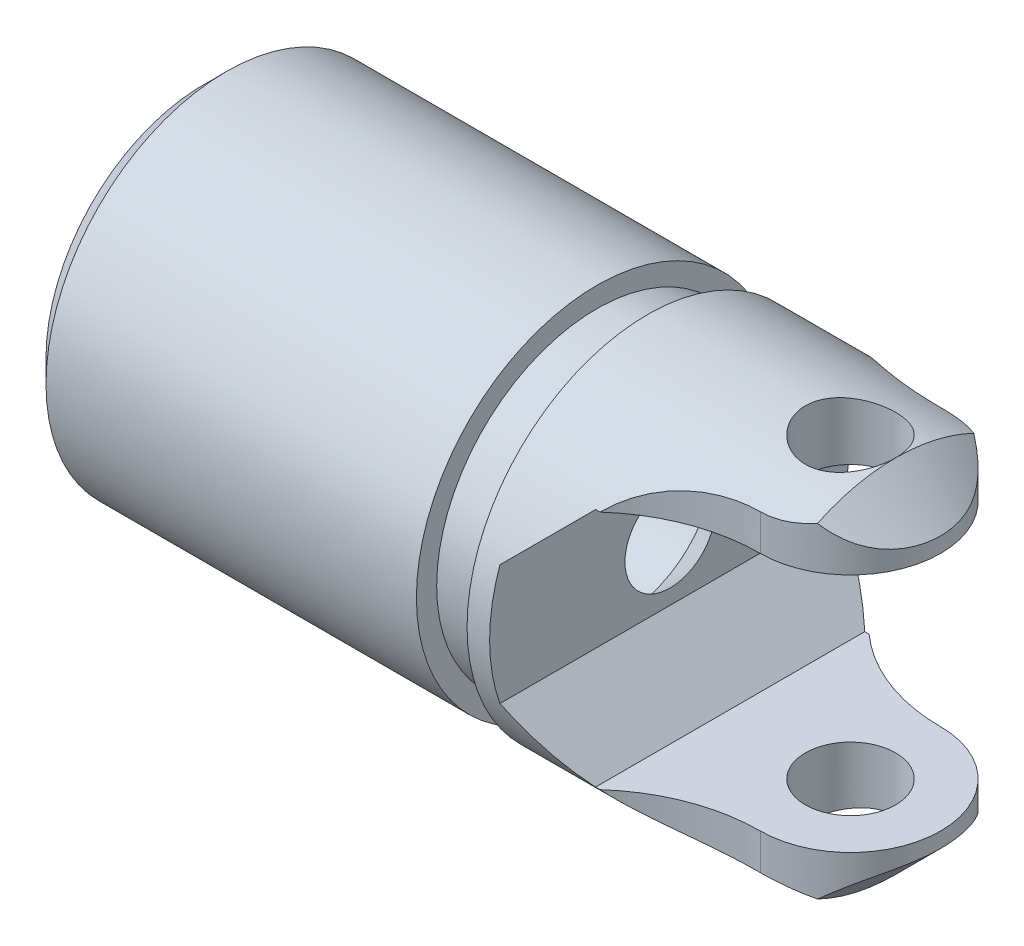
SolidWorks part; units mm, degrees
ref_plane "Front Plane" through (0, 0, 0) normal (0, 0, 1) x (1, 0, 0)
ref_plane "Top Plane" through (0, 0, 0) normal (0, 1, 0) x (1, 0, 0)
ref_plane "Right Plane" through (0, 0, 0) normal (1, 0, 0) x (0, 0, -1)
sketch "Sketch0" plane through (0, 0, 0) normal (0, 1, 0) x (1, 0, 0)
  line L0 (-34.1313, 0) -> (34.1313, 0) construction
  line L1 (-34.1313, 9.525) -> (-34.1313, -9.525) construction
  line L2 (-11.9063, 4.7625) -> (-11.9063, -4.7625) construction
  line L3 (-11.9063, 4.7625) -> (-7.1438, 0) construction
  line L4 (-7.1438, 0) -> (-11.9063, -4.7625) construction
  line L5 (-9.525, 2.3812) -> (-9.525, -2.3812) construction
  point P7 (-11.9063, 0)
  point P8 (0, 0)
  point P12 (-9.525, 0)
sketch "Sketch1" plane through (0, 0, 0) normal (0, 1, 0) x (1, 0, 0)
  line L0 (-34.1313, 9.525) -> (-13.3896, 9.525)
  line L1 (4.7625, 9.525) -> (4.7625, 0)
  line L2 (4.7625, 0) -> (-34.1313, 0)
  line L3 (-34.1313, 0) -> (-34.1313, 9.525)
  line L4 (-34.1313, 9.525) -> (-34.1313, -9.525) construction
  line L5 (-34.1313, 0) -> (34.1313, 0) construction
  line L6 (-10.7156, 9.525) -> (4.7625, 9.525)
  line L7 (-10.7156, 2.3812) -> (-10.7156, 8.4554) construction
  line L8 (-13.3896, 9.525) -> (-13.3896, 8.4554)
  line L9 (-13.3896, 8.4554) -> (-10.7156, 8.4554)
  line L10 (-10.7156, 9.525) -> (-10.7156, 8.4554)
  line L11 (0, 0) -> (9.525, 0) construction
  line L12 (-9.525, 2.3812) -> (-11.9063, 2.3812) construction
  line L13 (-11.9063, 4.7625) -> (-11.9063, -4.7625) construction
  circle A0 centre (0, 0) radius 9.525 construction
  dimension "D1" = 2.6739
  dimension "D2" = 1.0696
  dimension "D3" = 38.8937
revolve "Revolve1" add sketch "Sketch1" angle 360 about L0
chamfer "Chamfer1" distance 1.1906 angle 45 1 edges at (-34.1313, 0, 9.525)
chamfer "Chamfer2" distance 2.3813 angle 45 1 edges at (4.7625, 0, 9.525)
sketch "Sketch2" plane through (0, 0, 0) normal (0, 1, 0) x (1, 0, 0)
  line L0 (-10.7156, 9.525) -> (-8.0417, 9.525) construction
  line L1 (-10.7156, 9.525) -> (4.7625, 9.525) construction
  line L2 (2.3813, 9.525) -> (-10.7156, 9.525) construction
  line L3 (-13.3896, 8.4554) -> (-10.7156, 8.4554) construction
  line L4 (-34.1313, 0) -> (4.7625, 0) construction
  line L5 (-8.0417, 9.525) -> (9.525, 9.525)
  line L6 (9.525, 9.525) -> (9.525, -9.525)
  line L7 (9.525, -9.525) -> (-8.0417, -9.525)
  line L8 (0, 4.7625) -> (0, 0) construction
  arc A0 (-8.0417, 9.525) -> (0, 4.7625) centre (0, 13.9331) ccw
  arc A1 (0, -4.7625) -> (0, 4.7625) centre (0, 0) ccw
  arc A2 (-8.0417, -9.525) -> (0, -4.7625) centre (0, -13.9331) cw
  dimension "D1" = 9.525
extrude "Extrude1" cut sketch "Sketch2" against normal through all and the other way through all
sketch "Sketch3" plane through (0, 0, 0) normal (0, 0, 1) x (1, 0, 0)
  line L0 (-6.3532, 6.3436) -> (-9.525, 3.1718)
  line L1 (-6.3532, 6.3436) -> (9.525, 6.3437)
  line L2 (-9.525, 3.1718) -> (-9.525, -3.1718)
  line L3 (-6.3532, -6.3436) -> (9.525, -6.3437)
  line L4 (9.525, 6.3437) -> (9.525, -6.3437)
  line L5 (-9.525, -3.1718) -> (-6.3532, -6.3436)
  dimension "D1" = 12.6873
  dimension "D2" = 3.1718
extrude "Extrude3" cut sketch "Sketch3" against normal through all and the other way through all
sketch "Sketch4" plane through (-34.1313, 0, 0) normal (-1, 0, 0) x (0, 0, 1)
  circle A0 centre (0, 0) radius 4.7625
extrude "Extrude4" cut sketch "Sketch4" against normal up to vertex (22.225 mm away) up to point (-11.9063, 0, -4.7625)
sketch "Sketch5" plane through (-11.9063, 0, 0) normal (-1, 0, 0) x (0, 0, 1)
  circle A0 centre (0, 0) radius 4.7625 construction
  circle A1 centre (0, 0) radius 4.7625
extrude "Extrude5" cut sketch "Sketch5" against normal through all draft 45
sketch "Sketch6" plane through (0, 0, 0) normal (0, 1, 0) x (1, 0, 0)
  line L0 (-34.1313, 0) -> (34.1313, 0) construction
  line L1 (4.7625, 0) -> (2.3812, 0) construction
  line L2 (2.3812, 0) -> (0, 0) construction
  circle A0 centre (0, 0) radius 2.3812
  arc A1 (0, -4.7625) -> (0, 4.7625) centre (0, 0) ccw construction
  dimension "D1" = 4.7625
extrude "Extrude6" cut sketch "Sketch6" against normal through all and the other way through all
mirror "Mirror1" [suppressed] about plane through (0, 0, 0) normal (1, 0, 0)
move or copy body "Body-Move/Copy1" [suppressed] bodies to move or copy 110 copy no rotation origin (0, 0, 0) rotation axis (1, 0, 0) rotation angle 90
sketch "Sketch18" [suppressed] plane through (0, 0, 0) normal (0, 1, 0) x (1, 0, 0)
  line L0 (-47.625, -4.7625) -> (-11.9063, -4.7625)
  line L3 (-47.625, 4.7625) -> (-11.9063, 4.7625)
  line L4 (-11.9063, 4.7625) -> (-11.9063, -4.7625)
  line L5 (11.9063, 4.7625) -> (11.9063, -4.7625)
  line L6 (11.9063, -4.7625) -> (34.1313, -4.7625)
  line L7 (11.9063, 4.7625) -> (34.1313, 4.7625)
  line L8 (0, 0) -> (11.9063, 0) construction
  line L9 (34.1313, -8.3344) -> (34.1313, 8.3344) construction
  line L11 (-11.9063, -4.7625) -> (-11.9063, 4.7625) construction
sketch "Sketch10" plane through (0, 0, 0) normal (0, 0, 1) x (1, 0, 0)
  line L0 (-6.3532, 6.3436) -> (6.3532, -6.3437) construction
  line L1 (-6.3532, 6.3436) -> (6.3532, 6.3436)
  line L2 (-6.3532, 6.3436) -> (-6.3532, -6.3437)
  line L3 (-6.3532, -6.3437) -> (6.3532, -6.3437)
  line L4 (6.3532, 6.3436) -> (6.3532, -6.3437)
  line L5 (0, 6.3436) -> (4.7625, 6.3436) construction
extrude "Extrude10" [suppressed] add sketch "Sketch10" against normal up to surface and the other way up to surface separate body
sketch "Sketch11" [suppressed] plane through (6.3532, 0, 0) normal (1, 0, 0) x (0, 0, -1)
  line L4 (-6.3436, -6.3437) -> (-6.3437, 6.3436) construction
  circle A0 centre (0, 0) radius 6.3436
extrude "Extrude11" [suppressed] cut sketch "Sketch11" against normal through all draft 60 flip side to cut
sketch "Sketch12" [suppressed] plane through (-6.3532, -21.0185, 0) normal (1, 0, 0) x (0, -1, 0)
  circle A2 centre (-21.0185, 0) radius 6.3436
  circle A6 centre (-21.0185, 0) radius 6.3436
  dimension "D1" = 0
extrude "Extrude12" [suppressed] cut sketch "Sketch12" along normal through all draft 60 flip side to cut
sketch "Sketch13" plane through (0, 0, 0) normal (0, 1, 0) x (1, 0, 0)
  circle A0 centre (0, 0) radius 2.3812 construction
  circle A1 centre (0, 0) radius 2.3812
extrude "Extrude13" [suppressed] cut sketch "Sketch13" against normal through all and the other way through all
sketch "Sketch14" plane through (0, 0, 0) normal (0, 1, 0) x (1, 0, 0)
  circle A1 centre (0, 0) radius 2.3812
  circle A2 centre (0, 0) radius 2.3812
  dimension "D1" = 0
extrude "Extrude14" [suppressed] add sketch "Sketch14" along normal mid plane 19.05 separate body
sketch "Sketch15" [suppressed] plane through (0, 0, 0) normal (0, 0, 1) x (1, 0, 0)
  circle A0 centre (0, 0) radius 2.3812 construction
  circle A1 centre (0, 0) radius 2.3812
extrude "Extrude15" [suppressed] cut sketch "Sketch15" against normal through all and the other way through all
sketch "Sketch16" [suppressed] plane through (0, 0, 0) normal (0, 0, 1) x (1, 0, 0)
  circle A1 centre (0, 0) radius 2.3812
  circle A2 centre (0, 0) radius 2.3812
  dimension "D1" = 0
extrude "Extrude16" [suppressed] add sketch "Sketch16" along normal mid plane 19.05
chamfer "Chamfer3" [suppressed] distance 0.5953 angle 45
move or copy body "Body-Move/Copy2" [suppressed] bodies to move or copy 111 copy no rotation origin (0, 0, 0) rotation axis (0, 0, -1) rotation angle 25
equation "\"D2@Sketch3\" = \"D1@Sketch3\" / 4"
equation "\"D1@Extrude14\" = \"OD@Sketch0\""
equation "\"D1@Extrude16\" = \"D1@Extrude14\""
equation "\"D1@Sketch3\" = \"OD@Sketch0\"*.666"
equation "\"D2@Sketch3\" = \"D1@Sketch3\"/4"
equation "\"D1@Sketch1\" = \"D3@Sketch1\"*.06875"
equation "\"D2@Sketch1\" = \"D1@Sketch1\"/2.5"
equation "\"D1@Chamfer1\" = \"OD@Sketch0\"/16"
equation "\"D1@Chamfer2\" = \"D1@Chamfer1\"*2"
equation "\"D1@Chamfer3\" = \"D1@Chamfer1\"*.50"
